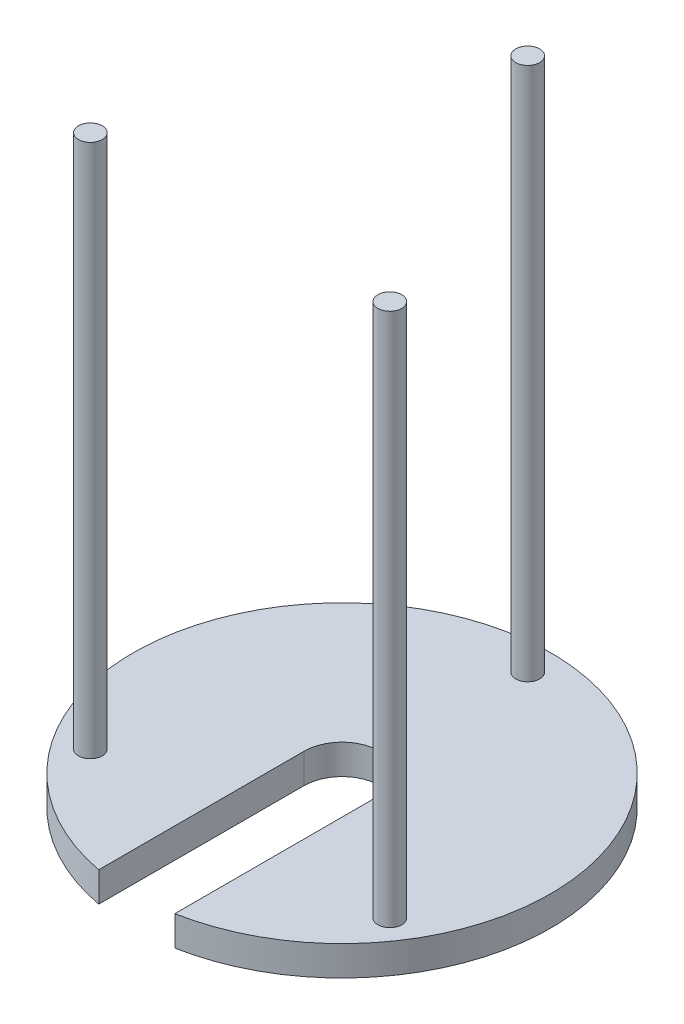
SolidWorks part; units mm, degrees
ref_plane "前视基准面" through (0, 0, 0) normal (0, 0, 1) x (1, 0, 0)
ref_plane "上视基准面" through (0, 0, 0) normal (0, 1, 0) x (1, 0, 0)
ref_plane "右视基准面" through (0, 0, 0) normal (1, 0, 0) x (0, 0, -1)
other "Configuration Table"
sketch "草图1" plane through (0, 0, 0) normal (0, 1, 0) x (1, 0, 0)
  circle A0 centre (0, 0) radius 70
extrude "凸台-拉伸1" add sketch "草图1" along normal blind 10
sketch "草图2" plane through (0, 10, 0) normal (0, 1, 0) x (1, 0, 0)
  circle A0 centre (-49.2265, -35.171) radius 4
  circle A1 centre (1.7675, 60.5) radius 4
  circle A2 centre (50.0353, -34.0105) radius 4
  point P2 (0, 0)
  point P7 (0, 0)
  point P11 (1.7675, 3.0932)
  dimension "D1" = 60.5
  dimension "D2" = 60.5
  dimension "D3" = 60.5
extrude "凸台-拉伸4" add sketch "草图2" along normal blind 179
sketch "草图5" plane through (0, 10, 0) normal (0, 1, 0) x (1, 0, 0)
  line L1 (-12.75, 0) -> (12.75, 0)
  line L2 (-12.75, 0) -> (-12.75, -74.3448)
  line L3 (-12.75, -74.3448) -> (12.75, -74.3448)
  line L4 (12.75, 0) -> (12.75, -74.3448)
  circle A0 centre (0, 0) radius 12.75
  dimension "D1" = 25.5
extrude "切除-拉伸1" cut sketch "草图5" against normal blind 10 contours A0 | L4 L3 L2 L1
